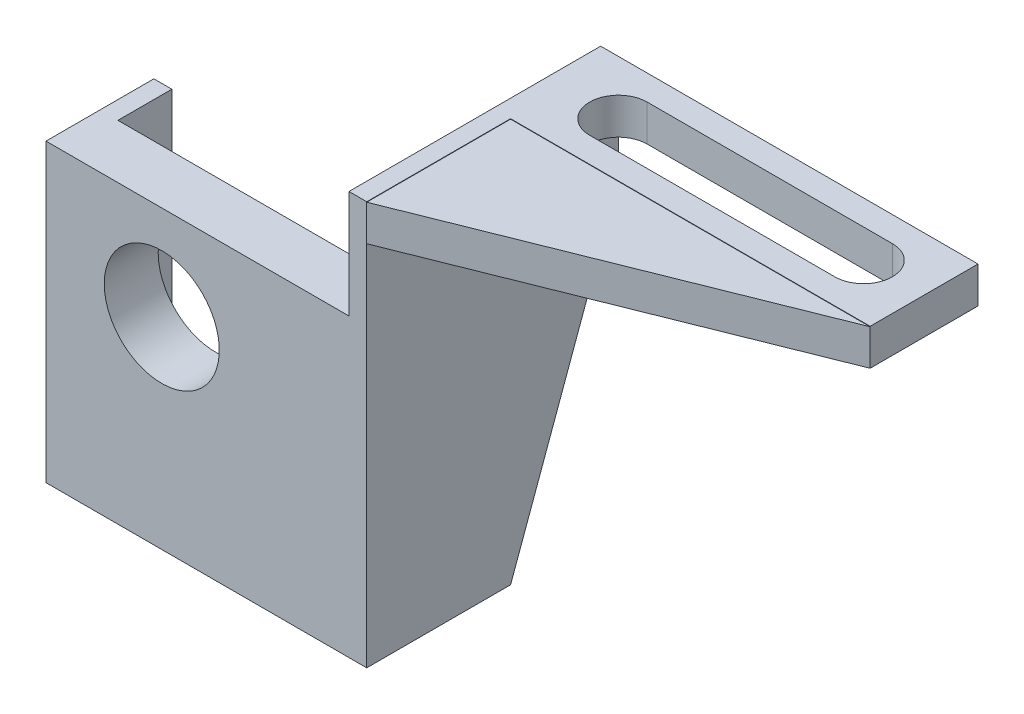
SolidWorks part; units mm, degrees
ref_plane "Front Plane" through (0, 0, 0) normal (0, 0, 1) x (1, 0, 0)
ref_plane "Top Plane" through (0, 0, 0) normal (0, 1, 0) x (1, 0, 0)
ref_plane "Right Plane" through (0, 0, 0) normal (1, 0, 0) x (0, 0, -1)
sketch "Sketch2" plane through (0, 0, 0) normal (0, 0, 1) x (1, 0, 0)
  line L0 (-6.5238, 2.0903) -> (0.8762, 2.0903) construction
  line L1 (-6.5238, 7.3453) -> (6.8762, 7.3453)
  line L2 (-6.5238, 7.3453) -> (-6.5238, -3.1647)
  line L3 (-6.5238, -3.1647) -> (6.8762, -3.1647)
  line L4 (6.8762, 7.3453) -> (6.8762, -3.1647)
  circle A0 centre (0.8762, 2.0903) radius 3.2
  dimension "D4" = 6.4
  dimension "D1" = 13.4
  dimension "D2" = 10.51
  dimension "D3" = 7.4
extrude "Boss-Extrude1" add sketch "Sketch2" along normal blind 3
sketch "Sketch4" plane through (0, 0, 3) normal (0, 0, 1) x (1, 0, 0)
  line L0 (0.8762, -1.1097) -> (0.8762, -9.1097) construction
  line L2 (-6.5238, -3.1647) -> (6.8832, -3.1647)
  line L3 (-6.5238, -3.1647) -> (-6.5238, -9.1097)
  line L4 (-6.5238, -9.1097) -> (6.8832, -9.1097)
  line L5 (6.8832, -3.1647) -> (6.8832, -9.1097)
  circle A0 centre (0.8762, 2.0903) radius 3.2 construction
  dimension "D1" = 8
extrude "Boss-Extrude3" add sketch "Sketch4" against normal blind 3
sketch "Sketch5" plane through (0, 0, 0) normal (0, 0, -1) x (-1, 0, 0)
  line L0 (-0.8762, -1.1097) -> (-0.8762, -6.0797) construction
  circle A0 centre (-0.8762, 2.0903) radius 3.2 construction
  circle A1 centre (-0.8762, -6.0797) radius 1.65
  dimension "D2" = 3.3
  dimension "D1" = 4.97
extrude "Boss-Extrude4" add sketch "Sketch5" along normal blind 3
sketch "Sketch6" plane through (-6.5238, 0, 0) normal (-1, 0, 0) x (0, 0, 1)
  line L0 (0, -7.4091) -> (0, 7.4091) construction
  line L1 (0, 7.3453) -> (3, 7.3453)
  line L2 (0, 7.3453) -> (0, -9.1097)
  line L3 (0, -9.1097) -> (3, -9.1097)
  line L4 (3, 7.3453) -> (3, -9.1097)
  line L5 (3, 7.3453) -> (0, 7.3453) construction
extrude "Boss-Extrude5" add sketch "Sketch6" along normal blind 4
sketch "Sketch7" plane through (0, 0, 0) normal (0, 0, -1) x (-1, 0, 0)
  line L0 (10.5238, -9.1097) -> (-6.8832, -9.1097) construction
  line L1 (10.5238, 7.3453) -> (9.5238, 7.3453)
  line L2 (10.5238, 7.3453) -> (10.5238, -9.1097)
  line L3 (10.5238, -9.1097) -> (9.5238, -9.1097)
  line L4 (9.5238, 7.3453) -> (9.5238, -9.1097)
  dimension "D1" = 1
extrude "Boss-Extrude6" add sketch "Sketch7" along normal blind 5
sketch "Sketch11" plane through (0, 7.3453, 0) normal (0, 1, 0) x (1, 0, 0)
  line L0 (6.8762, -3) -> (-10.5238, -3) construction
  line L1 (-10.5238, 5) -> (-9.5355, 5)
  line L2 (-10.5238, 5) -> (-10.5238, -3)
  line L3 (-10.5238, -3) -> (-9.5355, -3)
  line L4 (-9.5355, 5) -> (-9.5355, -3)
extrude "Boss-Extrude8" add sketch "Sketch11" along normal blind 6
sketch "Sketch16" plane through (0, 0, -5) normal (0, 0, -1) x (-1, 0, 0)
  line L0 (10.5238, -9.1097) -> (10.5238, 13.3453) construction
  line L1 (9.5355, 13.3453) -> (10.5238, 13.3453)
  line L2 (9.5355, 13.3453) -> (9.5355, 7.3453)
  line L3 (9.5355, 7.3453) -> (10.5238, 7.3453)
  line L4 (10.5238, 13.3453) -> (10.5238, 7.3453)
  dimension "D1" = 6
extrude "Boss-Extrude12" add sketch "Sketch16" along normal blind 6
sketch "Sketch17" plane through (-10.5238, 0, 0) normal (-1, 0, 0) x (0, 0, 1)
  line L0 (-11, 7.3453) -> (-5, -9.1097)
  line L1 (-5, -9.1097) -> (-5, 7.3453)
  line L2 (-5, 7.3453) -> (-11, 7.3453)
extrude "Boss-Extrude13" add sketch "Sketch17" against normal blind 1
sketch "Sketch20" plane through (-10.5238, 0, 0) normal (-1, 0, 0) x (0, 0, 1)
  line L1 (-11, 13.3453) -> (-5, 13.3453)
  line L2 (-11, 13.3453) -> (-11, 11.3212)
  line L3 (-11, 11.3212) -> (-5, 11.3212)
  line L4 (-5, 13.3453) -> (-5, 11.3212)
  dimension "D1" = 6
extrude "Boss-Extrude15" add sketch "Sketch20" along normal blind 20
sketch "Sketch21" plane through (0, 11.3212, 0) normal (0, -1, 0) x (1, 0, 0)
  line L0 (-30.5238, -8) -> (-6.5602, -8) construction
  line L1 (-30.5238, -11) -> (-30.5238, -5) construction
  line L2 (-20.5238, -5) -> (-20.5238, -12.6331) construction
  line L3 (-30.5238, -5) -> (-10.5238, -5) construction
  line L4 (-27.1602, -8) -> (-13.5238, -8) construction
  line L5 (-27.1602, -6.4) -> (-13.5238, -6.4)
  line L6 (-27.1602, -9.6) -> (-13.5238, -9.6)
  line L7 (-10.5238, -11) -> (-10.5238, -5) construction
  arc A0 (-27.1602, -6.4) -> (-27.1602, -9.6) centre (-27.1602, -8) ccw
  arc A1 (-13.5238, -9.6) -> (-13.5238, -6.4) centre (-13.5238, -8) ccw
  point P10 (-20.342, -8)
  dimension "D1" = 3.2
  dimension "D2" = 3
extrude "Cut-Extrude3" cut sketch "Sketch21" against normal through all
sketch "Sketch22" plane through (6.8762, 0, 0) normal (1, 0, 0) x (0, 0, -1)
  line L1 (-3, 7.3453) -> (0, 7.3453)
  line L2 (-3, 7.3453) -> (-3, -9.1097)
  line L3 (-3, -9.1097) -> (0, -9.1097)
  line L4 (0, 7.3453) -> (0, -9.1097)
extrude "Boss-Extrude16" add sketch "Sketch22" along normal blind 0.44
sketch "Sketch23" plane through (0, 0, 0) normal (0, 0, -1) x (-1, 0, 0)
  line L0 (9.5238, -9.1097) -> (-7.3162, -9.1097) construction
  line L1 (-7.3162, 7.3453) -> (-6.3162, 7.3453)
  line L2 (-7.3162, 7.3453) -> (-7.3162, -9.1097)
  line L3 (-7.3162, -9.1097) -> (-6.3162, -9.1097)
  line L4 (-6.3162, 7.3453) -> (-6.3162, -9.1097)
  dimension "D1" = 1
extrude "Boss-Extrude17" add sketch "Sketch23" along normal blind 3
sketch "Sketch24" plane through (0, 11.3212, 0) normal (0, -1, 0) x (1, 0, 0)
  line L0 (-30.5238, -5) -> (-10.5238, -5)
  line L1 (-10.5238, -5) -> (-10.5238, 3)
  line L2 (-10.5238, 3) -> (-30.5238, -5)
  dimension "D1" = 8
extrude "Boss-Extrude18" add sketch "Sketch24" against normal blind 2
ref_plane "Plane1" through (-41.8897, 0, 0) normal (1, 0, 0) x (0, 0, -1)
mirror "Mirror1" about plane through (-41.8897, 0, 0) normal (1, 0, 0)
delete or keep bodies "Body-Delete/Keep 1" type delete bodies bodies 121
